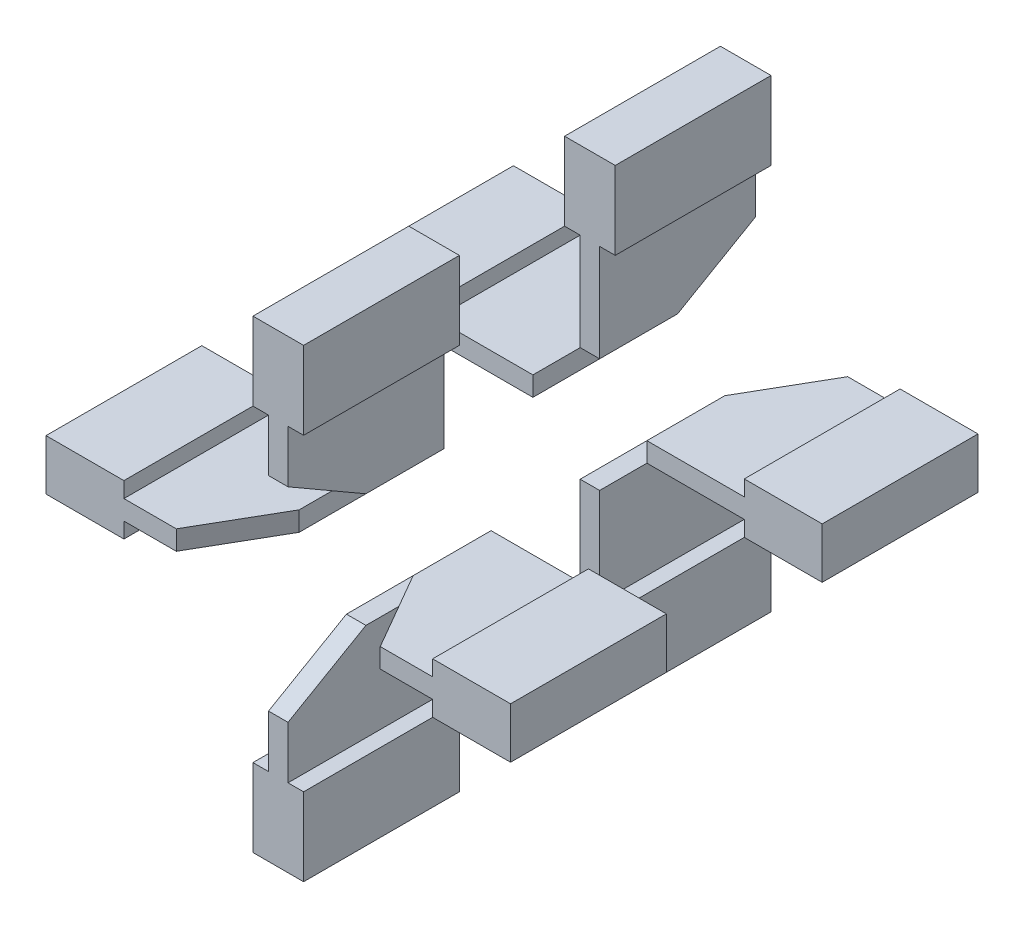
SolidWorks part; units mm, degrees
ref_plane "Front Plane" through (0, 0, 0) normal (0, 0, 1) x (1, 0, 0)
ref_plane "Top Plane" through (0, 0, 0) normal (0, 1, 0) x (1, 0, 0)
ref_plane "Right Plane" through (0, 0, 0) normal (1, 0, 0) x (0, 0, -1)
ref_plane "Plane1" through (0, 0, 20) normal (0, 0, 1) x (1, 0, 0)
sketch "Sketch3" plane through (0, 0, 0) normal (0, 0, 1) x (1, 0, 0)
  line L0 (0, 93.0232) -> (0, 12.7211)
sketch "Sketch4" plane through (0, 0, 20) normal (0, 0, 1) x (1, 0, 0)
  line L0 (0, 93.0232) -> (0, 12.7211) construction
  line L1 (-2.5, 30.3721) -> (2.5, 30.3721)
  line L2 (-2.5, 50.3721) -> (-2.5, 75.3721)
  line L3 (-2.5, 75.3721) -> (2.5, 75.3721)
  line L4 (2.5, 50.3721) -> (2.5, 75.3721)
  line L8 (-2.5, 50.3721) -> (-6.5, 50.3721)
  line L9 (-6.5, 50.3721) -> (-6.5, 30.3721)
  line L10 (-6.5, 30.3721) -> (-2.5, 30.3721)
  line L11 (2.5, 50.3721) -> (6.5, 50.3721)
  line L12 (6.5, 50.3721) -> (6.5, 30.3721)
  line L13 (6.5, 30.3721) -> (2.5, 30.3721)
  point P0 (0, 52.8721)
sketch "Sketch5" plane through (0, 0, 20) normal (0, 0, 1) x (1, 0, 0)
  line L0 (-5.3896, 95.3721) -> (5.3856, 95.3721)
  line L3 (0, 0.3721) -> (0.822, 0.3721) construction
  line L5 (-2.5, 30.3721) -> (2.5, 30.3721) construction
  point P6 (0, 0)
  dimension "D1" = 30
ref_plane "Plane2" through (0, 90, 0) normal (0, 1, 0) x (1, 0, 0)
sketch "Sketch6" plane through (0, 90, 0) normal (0, 1, 0) x (1, 0, 0)
  line L0 (0, -19.3575) -> (0, 0)
extrude "Boss-Extrude1" add sketch "Sketch4" along normal blind 40
sketch "Sketch7" plane through (2.5, 0, 0) normal (1, 0, 0) x (0, 0, -1)
  line L0 (-60, 75.3721) -> (-60, 63.8251) construction
  line L3 (-60, 50.3721) -> (-60, 75.3721) construction
  line L4 (-60, 63.8251) -> (-40, 75.3721) construction
  line L5 (-60, 75.3721) -> (-20, 75.3721) construction
  line L6 (-60, 63.8251) -> (-60, 75.3721)
  line L7 (-60, 75.3721) -> (-40, 75.3721)
  line L8 (-40, 75.3721) -> (-60, 63.8251)
  dimension "D1" = 60
extrude "Cut-Extrude1" cut sketch "Sketch7" against normal through all
pattern_circular "CirPattern1" count 4 over 360 about axis through (0, 90, 0) along (0, 0, 1) of "Boss-Extrude1"
sketch "Sketch8" plane through (0, 0, 20) normal (0, 0, -1) x (-1, 0, 0)
  point P0 (0, 90)
ref_plane "Plane3" through (0, 0, 0) normal (0, 0, -1) x (-1, 0, 0)
mirror "Mirror8" about plane through (0, 0, 0) normal (0, 0, -1) of bodies 105 102 103 104
sketch "Sketch9" plane through (0, 0, 20) normal (0, 0, -1) x (-1, 0, 0)
  point P0 (0, 90)
